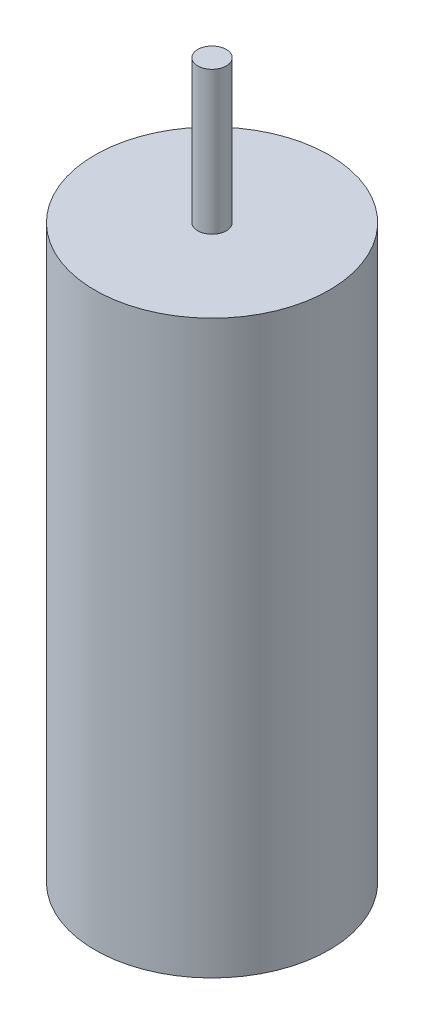
SolidWorks part; units mm, degrees
material "1.4000 (X6Cr13)"
ref_plane "Plano frontal" through (0, 0, 0) normal (0, 0, 1) x (1, 0, 0)
ref_plane "Plano superior" through (0, 0, 0) normal (0, 1, 0) x (1, 0, 0)
ref_plane "Plano direito" through (0, 0, 0) normal (1, 0, 0) x (0, 0, -1)
sketch "Esboço1" plane through (0, 0, 0) normal (0, 0, 1) x (1, 0, 0)
  line L0 (0, 25) -> (0.5, 25)
  line L1 (0.5, 25) -> (0.5, 20)
  line L2 (0.5, 20) -> (4.1, 20)
  line L3 (4.1, 20) -> (4.1, 0)
  line L4 (4.1, 0) -> (0, 0)
  line L5 (0, 0) -> (0, 25) construction
  line L6 (0, 25) -> (0, 0)
  dimension "D1" = 1
  dimension "D2" = 8.2
  dimension "D3" = 20
  dimension "D4" = 5
revolve "Revolução1" add sketch "Esboço1" angle 360 about L5
